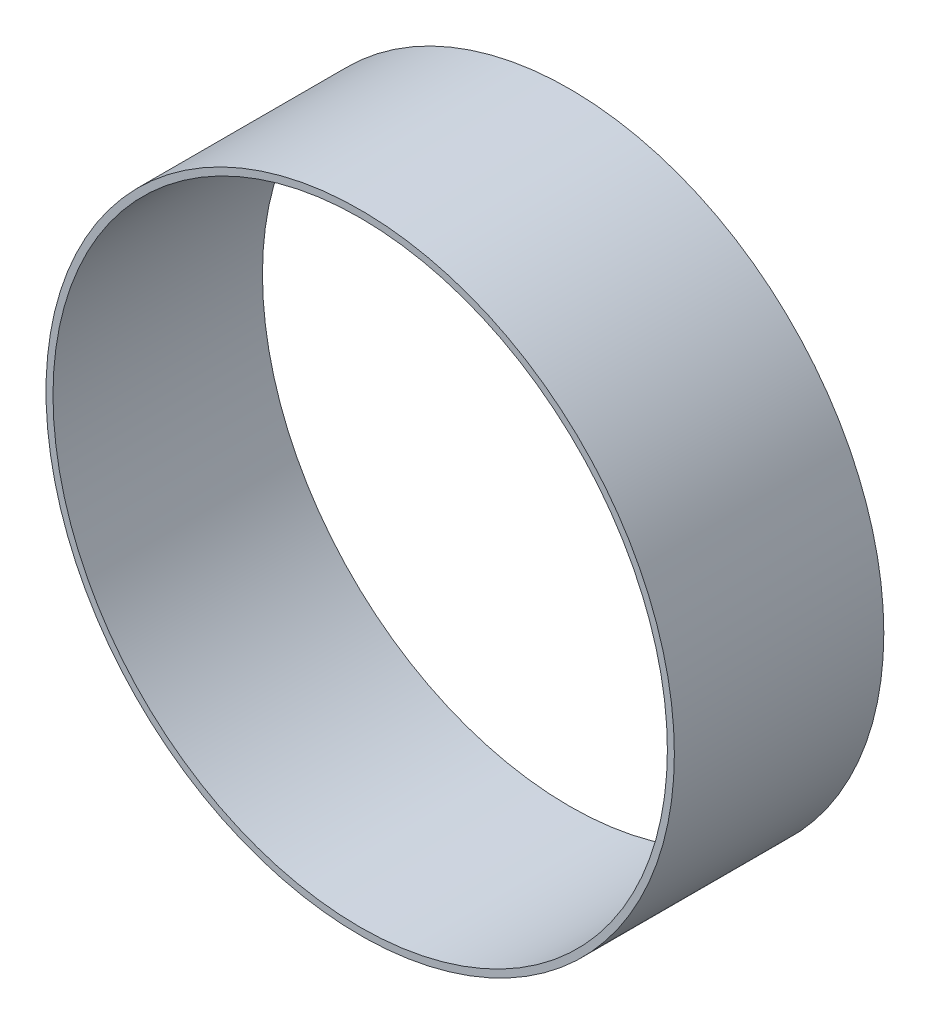
SolidWorks part; units mm, degrees
ref_plane "Front Plane" through (0, 0, 0) normal (0, 0, 1) x (1, 0, 0)
ref_plane "Top Plane" through (0, 0, 0) normal (0, 1, 0) x (1, 0, 0)
ref_plane "Right Plane" through (0, 0, 0) normal (1, 0, 0) x (0, 0, -1)
sketch "Sketch1" plane through (0, 0, 0) normal (0, 0, 1) x (1, 0, 0)
  circle A0 centre (0, 0) radius 139.7
  circle A1 centre (0, 0) radius 142.875
  dimension "D1" = 279.4
  dimension "D2" = 285.75
extrude "Boss-Extrude1" add sketch "Sketch1" along normal blind 95.25
